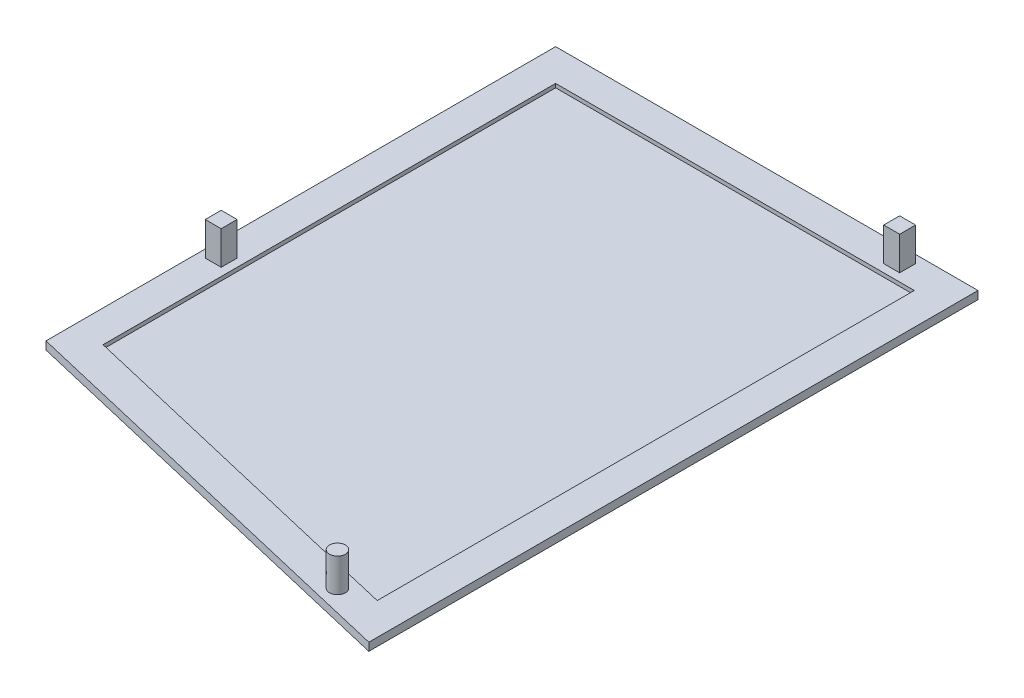
SolidWorks part; units mm, degrees
ref_plane "Front Plane" through (0, 0, 0) normal (0, 0, 1) x (1, 0, 0)
ref_plane "Top Plane" through (0, 0, 0) normal (0, 1, 0) x (1, 0, 0)
ref_plane "Right Plane" through (0, 0, 0) normal (1, 0, 0) x (0, 0, -1)
sketch "Sketch1" plane through (0, 0, 0) normal (0, 1, 0) x (1, 0, 0)
  line L0 (0, 0) -> (0, 80)
  line L1 (0, 80) -> (66.3, 80)
  line L2 (66.3, 80) -> (66.3, -15.6238)
  line L3 (66.3, -15.6238) -> (0, 0)
  dimension "D1" = 66.3
  dimension "D2" = 103.26
  dimension "D3" = 80
extrude "Boss-Extrude1" add sketch "Sketch1" along normal blind 1.25
sketch "Sketch2" plane through (0, 0, 0) normal (0, -1, 0) x (1, 0, 0)
  line L0 (0, -80) -> (0, 0) construction
  line L1 (0, 0) -> (66.3, 15.6238) construction
  line L2 (66.3, -80) -> (0, -80) construction
  line L3 (57.75, -78.75) -> (55.25, -78.75)
  line L4 (57.75, -78.75) -> (57.75, -76.25)
  line L5 (57.75, -76.25) -> (55.25, -76.25)
  line L6 (55.25, -78.75) -> (55.25, -76.25)
  line L7 (3.75, -26.25) -> (1.25, -26.25)
  line L8 (3.75, -26.25) -> (3.75, -23.75)
  line L9 (3.75, -23.75) -> (1.25, -23.75)
  line L10 (1.25, -26.25) -> (1.25, -23.75)
  circle A0 centre (56.5, 10.7459) radius 1.25
  point P14 (55.25, -77.5)
  dimension "D1" = 56.5
  dimension "D2" = 2.5
  dimension "D3" = 2.5
  dimension "D4" = 55.25
  dimension "D5" = 2.5
  dimension "D6" = 2.5
  dimension "D7" = 1.25
  dimension "D8" = 2.5
  dimension "D9" = 2.5
  dimension "D10" = 1.25
  dimension "D11" = 53.75
extrude "Boss-Extrude2" add sketch "Sketch2" against normal blind 6.5
sketch "Sketch4" plane through (0, 1.25, 0) normal (0, 1, 0) x (1, 0, 0)
  line L0 (5, 75) -> (5, 3.9587)
  line L1 (5, 3.9587) -> (61.3, -9.3086)
  line L2 (61.3, -9.3086) -> (61.3, 75)
  line L3 (61.3, 75) -> (5, 75)
  line L4 (66.3, 80) -> (0, 80) construction
  line L5 (0, 80) -> (0, 0) construction
  line L6 (66.3, -15.6238) -> (66.3, 80) construction
  line L7 (0, 0) -> (66.3, -15.6238) construction
  point P8 (18.9676, 58.2608)
  dimension "D1" = 5
  dimension "D2" = 5
  dimension "D3" = 5
  dimension "D4" = 5
  dimension "D5" = 5
  dimension "D6" = 5
  dimension "D7" = 5
extrude "Cut-Extrude1" cut sketch "Sketch4" against normal blind 0.6
